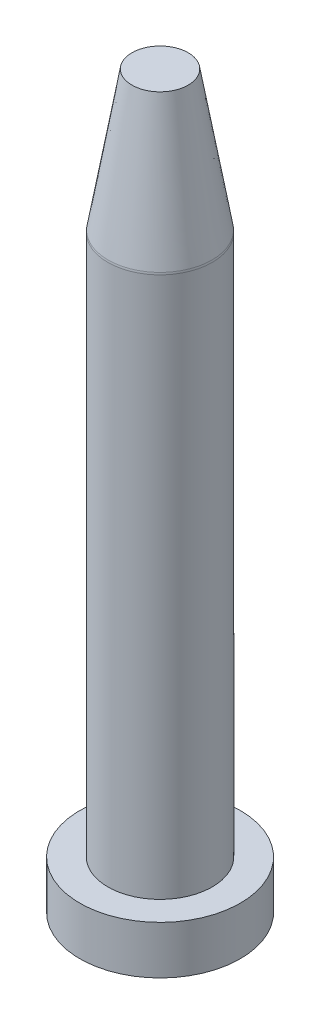
SolidWorks part; units mm, degrees
ref_plane "前视" through (0, 0, 0) normal (0, 0, 1) x (1, 0, 0)
ref_plane "上视" through (0, 0, 0) normal (0, 1, 0) x (1, 0, 0)
ref_plane "右视" through (0, 0, 0) normal (1, 0, 0) x (0, 0, -1)
sketch "草图1" plane through (0, 0, 0) normal (0, 0, 1) x (1, 0, 0)
  line L0 (0, 0) -> (0, 101.922) construction
  line L1 (0, 0) -> (20, 0)
  line L2 (20, 0) -> (20, 12)
  line L3 (20, 12) -> (13, 12)
  line L4 (13, 12) -> (13, 147)
  line L5 (0, 182) -> (7, 182)
  line L6 (7, 182) -> (13, 147)
  line L7 (0, 0) -> (0, 182)
  point P7 (0, 182)
  dimension "D1" = 20
  dimension "D2" = 12
  dimension "D3" = 7
  dimension "D4" = 135
  dimension "D5" = 182
  dimension "D6" = 7
revolve "基体-旋转" add sketch "草图1" angle 360 about L0
fillet "圆角1" radius 3 1 edges at (0, 147, -13)
